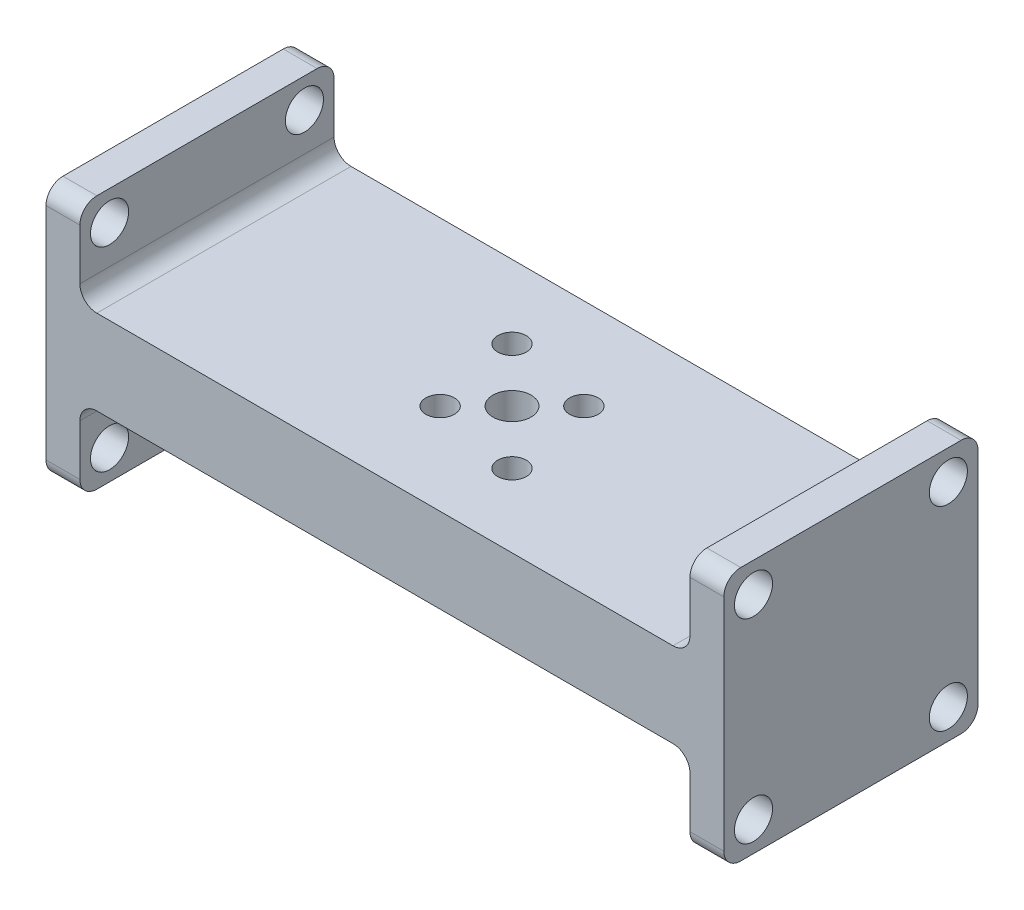
SolidWorks part; units mm, degrees
ref_plane "Front Plane" through (0, 0, 0) normal (0, 0, 1) x (1, 0, 0)
ref_plane "Top Plane" through (0, 0, 0) normal (0, 1, 0) x (1, 0, 0)
ref_plane "Right Plane" through (0, 0, 0) normal (1, 0, 0) x (0, 0, -1)
sketch "Sketch2" plane through (0, 0, 0) normal (0, 1, 0) x (1, 0, 0)
  line L0 (-4.2426, -4.2426) -> (4.2426, 4.2426) construction
  line L1 (-36, 15) -> (36, 15)
  line L2 (-36, 15) -> (-36, -15)
  line L3 (-36, -15) -> (36, -15)
  line L4 (36, 15) -> (36, -15)
  line L5 (6.364, -6.364) -> (-6.364, 6.364) construction
  circle A0 centre (0, 0) radius 2.25
  circle A1 centre (-6.364, 6.364) radius 1.6875
  circle A2 centre (6.364, -6.364) radius 1.6875
  circle A3 centre (4.2426, 4.2426) radius 1.6875
  circle A4 centre (-4.2426, -4.2426) radius 1.6875
  point P4 (0, 15)
  point P6 (-36, 0)
  point P12 (0, 0)
  point P15 (0, 0)
  dimension "D3" = 4.5
  dimension "D8" = 3.375
  dimension "D1" = 72
  dimension "D2" = 30
  dimension "D4" = 90
  dimension "D5" = 45
  dimension "D6" = 18
  dimension "D7" = 12
extrude "Boss-Extrude1" add sketch "Sketch2" along normal blind 10 contours A0 | A1 | L2 L3 L4 L1 | A4 | A3 | A2
sketch "Sketch3" plane through (-36, 0, 0) normal (-1, 0, 0) x (0, 0, 1)
  line L0 (-15, 10) -> (-15, 0) construction
  line L1 (-15, 20) -> (15, 20)
  line L2 (-15, 20) -> (-15, -10)
  line L3 (-15, -10) -> (15, -10)
  line L4 (15, 20) -> (15, -10)
  line L5 (15, 10) -> (15, 0) construction
  line L6 (-15, 10) -> (-15, 0) construction
  line L7 (0, 20) -> (0, -10) construction
  line L8 (-15, 5) -> (15, 5) construction
  circle A0 centre (-11.5, 16.5) radius 2.25
  circle A1 centre (-11.5, -6.5) radius 2.25
  circle A2 centre (11.5, -6.5) radius 2.25
  circle A3 centre (11.5, 16.5) radius 2.25
  point P8 (-15, 5)
  point P9 (-15, 5)
  dimension "D4" = 4.5
  dimension "D1" = 30
  dimension "D2" = 3.5
  dimension "D3" = 3.5
extrude "Boss-Extrude2" add sketch "Sketch3" along normal blind 4 contours A0 | A3 | A1 | A2 | L2 L3 L4 L1
mirror "Mirror1" about plane through (0, 0, 0) normal (1, 0, 0) of "Boss-Extrude2"
fillet "Fillet1" radius 2 4 edges at (-36, 10, 0) (-36, 0, 0) (36, 0, 0) (36, 10, 0)
fillet "Fillet2" radius 2 8 edges at (38, -10, -15) (38, -10, 15) (-38, -10, -15) (38, 20, 15) (38, 20, -15) (-38, -10, 15) (-38, 20, 15) (-38, 20, -15)
